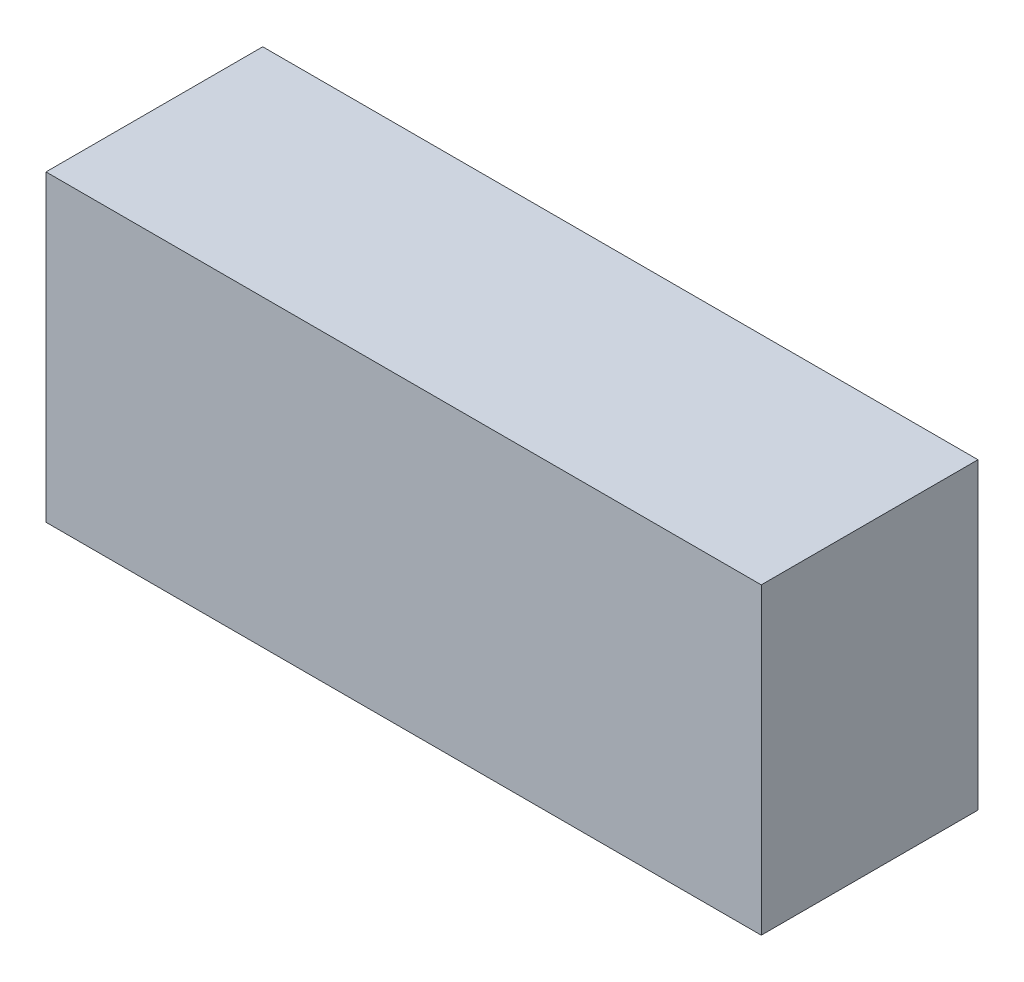
SolidWorks part; units mm, degrees
ref_plane "前视基准面" through (0, 0, 0) normal (0, 0, 1) x (1, 0, 0)
ref_plane "上视基准面" through (0, 0, 0) normal (0, 1, 0) x (1, 0, 0)
ref_plane "右视基准面" through (0, 0, 0) normal (1, 0, 0) x (0, 0, -1)
other "Configuration Table"
sketch "草图1" plane through (0, 0, 0) normal (0, 0, 1) x (1, 0, 0)
  line L1 (-82.5, -35) -> (82.5, -35)
  line L2 (-82.5, -35) -> (-82.5, 35)
  line L3 (-82.5, 35) -> (82.5, 35)
  line L4 (82.5, -35) -> (82.5, 35)
  line L5 (-82.5, -35) -> (82.5, 35) construction
  line L6 (-82.5, 35) -> (82.5, -35) construction
  point P0 (0, 0)
extrude "凸台-拉伸1" add sketch "草图1" along normal blind 50
